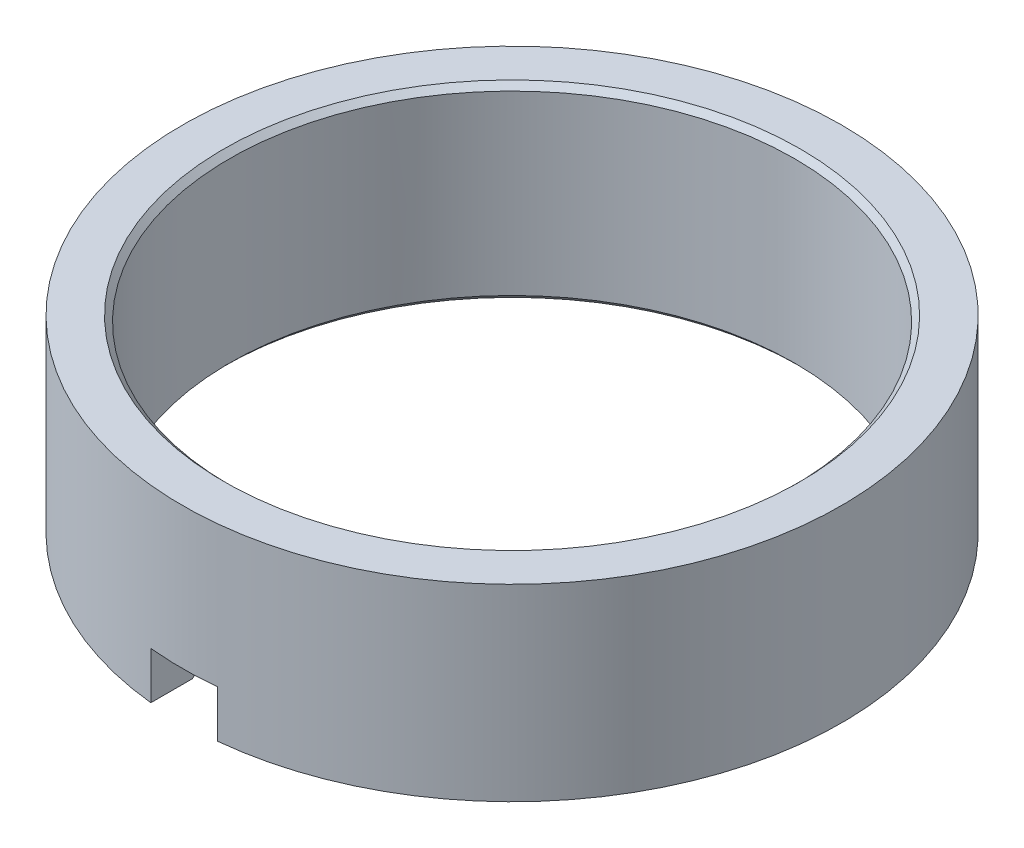
SolidWorks part; units mm, degrees
ref_plane "Front Plane" through (0, 0, 0) normal (1, 0, 0) x (0, 1, 0)
ref_plane "Top Plane" through (0, 0, 0) normal (0, 0, 1) x (0, 1, 0)
ref_plane "Right Plane" through (0, 0, 0) normal (0, 1, 0) x (-1, 0, 0)
sketch "Sketch1" plane through (0, 0, 0) normal (0, 0, 1) x (0, 1, 0)
  line L0 (-38.1, 133.35) -> (38.1, 133.35)
  line L1 (38.1, 133.35) -> (38.1, 114.3254)
  line L2 (38.1, 114.3254) -> (-38.1, 114.3254)
  line L3 (-38.1, 114.3254) -> (-38.1, 133.35)
  line L4 (-63.5, 0) -> (63.5, 0) construction
revolve "Revolve1" add sketch "Sketch1" angle 360 about L4
chamfer "Chamfer1" distance 2.286 angle 45 2 edges at (0, 38.1, -114.3254) (0, -38.1, -114.3254)
sketch "Sketch2" plane through (0, 0, 0) normal (0, 1, 0) x (-1, 0, 0)
  line L1 (-13.4874, 0) -> (13.4874, 0)
  line L2 (-13.4874, 0) -> (-13.4874, 266.7)
  line L3 (-13.4874, 266.7) -> (13.4874, 266.7)
  line L4 (13.4874, 0) -> (13.4874, 266.7)
extrude "Cut-Extrude2" cut sketch "Sketch2" along normal blind 19.05 from offset 38.1
